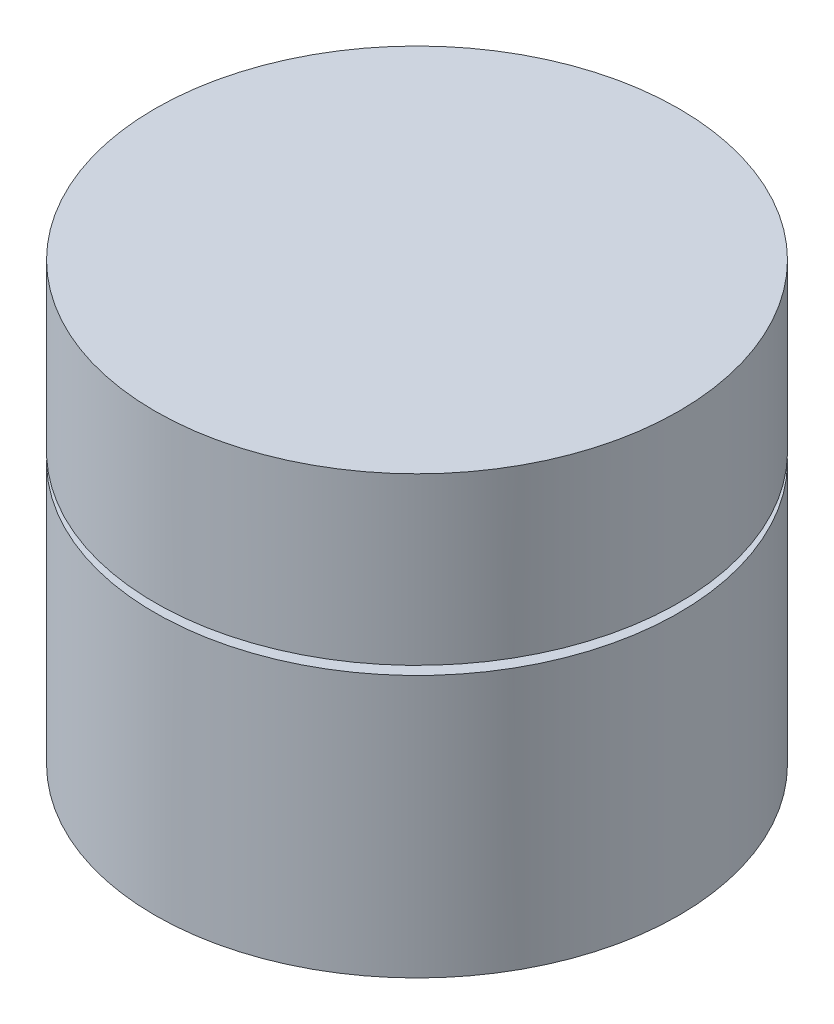
SolidWorks part; units mm, degrees
ref_plane "Front Plane" through (0, 0, 0) normal (0, 0, 1) x (1, 0, 0)
ref_plane "Top Plane" through (0, 0, 0) normal (0, 1, 0) x (1, 0, 0)
ref_plane "Right Plane" through (0, 0, 0) normal (1, 0, 0) x (0, 0, -1)
sketch "Sketch1" plane through (0, 0, 0) normal (0, 1, 0) x (1, 0, 0)
  circle A0 centre (0, 0) radius 3
  dimension "D1" = 6
extrude "Boss-Extrude1" add sketch "Sketch1" along normal blind 5
sketch "Sketch2" plane through (0, 0, 0) normal (0, 0, 1) x (1, 0, 0)
  line L0 (3, 0) -> (3, 5) construction
  line L1 (3, 3.1) -> (2.75, 3.1)
  line L2 (3, 3.1) -> (3, 3)
  line L3 (3, 3) -> (2.75, 3)
  line L4 (2.75, 3.1) -> (2.75, 3)
  line L5 (-3, 0) -> (3, 0) construction
  line L6 (0, 0) -> (0, 6.3019) construction
  dimension "D1" = 0.1
  dimension "D2" = 0.25
  dimension "D3" = 3
revolve "Cut-Revolve1" cut sketch "Sketch2" angle 360 about L6
